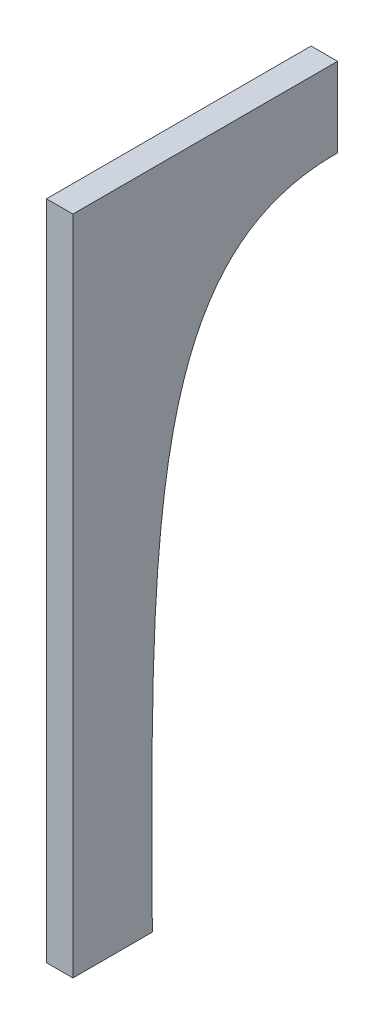
SolidWorks part; units mm, degrees
material "Balsa"
ref_plane "Front Plane" through (0, 0, 0) normal (0, 0, 1) x (1, 0, 0)
ref_plane "Top Plane" through (0, 0, 0) normal (0, 1, 0) x (1, 0, 0)
ref_plane "Right Plane" through (0, 0, 0) normal (1, 0, 0) x (0, 0, -1)
sketch "Sketch1" plane through (0, 0, 0) normal (1, 0, 0) x (0, 0, -1)
  line L0 (0, 0) -> (0, 317.5)
  line L1 (0, 317.5) -> (127, 317.5)
  line L2 (127, 317.5) -> (127, 279.4)
  line L3 (0, 0) -> (38.1, 0)
  spline S0 degree 3 poles (38.1, 0) (36.9394, 172.8674) (37.3012, 280.2383) (127, 279.4) knots 0 0 0 0 1 1 1 1
  dimension "D1" = 127
  dimension "D2" = 317.5
  dimension "D3" = 38.1
  dimension "D4" = 38.1
extrude "Boss-Extrude1" add sketch "Sketch1" along normal blind 12.7
